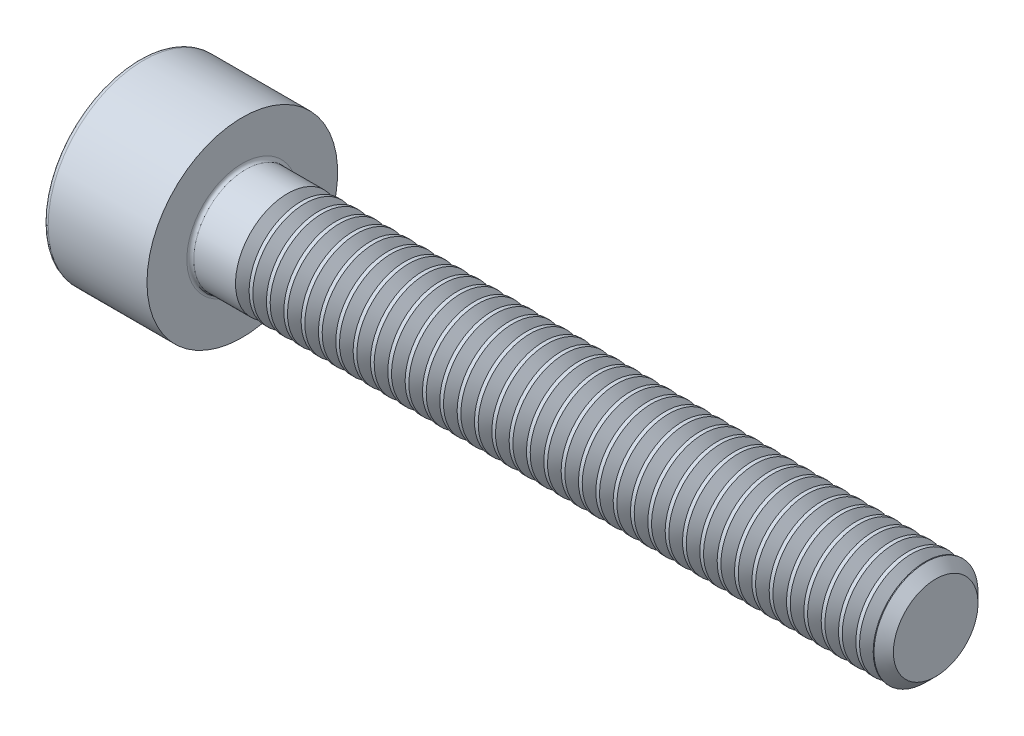
SolidWorks part; units mm, degrees
revolve "Base-Revolve" add sketch "BodySke"
sketch "BodySke" plane through (0, 0, 0) normal (0, 0, 1) x (1, 0, 0)
  line L0 (0, 0) -> (0, 2.75)
  line L1 (0, 2.75) -> (3, 2.75)
  line L2 (3, 2.75) -> (3, 1.5)
  line L3 (3, 1.5) -> (22.7195, 1.5)
  line L4 (23, 1.2195) -> (23, 0)
  line L5 (23, 0) -> (0, 0)
  line L6 (-31.75, 0) -> (127, 0) construction
  line L8 (23, 1.2195) -> (22.7195, 1.5)
  line L10 (23, -1.2195) -> (22.7195, -1.5) construction
  line L11 (3.5, 9.525) -> (3.5, 3.175) construction
  line L12 (3, 9.525) -> (3, 3.175) construction
  line L13 (-37, 9.525) -> (-37, 3.175) construction
  dimension "Body_ch_ang" = 45
  dimension "Thread_length" = 60
cosmetic thread "ThreadCosmetic" [suppressed]
fillet "Fillet1" radius 0.1 1 edges at (3, 0, 1.5)
fillet "Fillet2" radius 0.15 1 edges at (0, 0, 2.75)
ref_plane "Plane1" through (0, 0, 0) normal (0, 0, 1) x (1, 0, 0)
ref_plane "Plane2" through (0, 0, 0) normal (0, 1, 0) x (1, 0, 0)
ref_plane "Plane3" through (0, 0, 0) normal (1, 0, 0) x (0, 0, -1)
sketch "Sketch2" plane through (0, 0, 0) normal (0, 0, 1) x (1, 0, 0)
  line L0 (0, 1.28) -> (1.3, 1.28)
  line L1 (1.3, 1.28) -> (2.039, 0)
  line L2 (-31.75, 0) -> (127, 0) construction
  line L3 (2.039, 0) -> (0, 0)
  line L4 (0, 0) -> (0, 1.28)
  line L6 (0, 0) -> (47.625, 0) construction
  dimension "D2" = 60
  dimension "Depth" = 1.3
revolve "Hex-PreBroach" cut sketch "Sketch2" angle 360 about L6
sketch "Sketch3" plane through (0, 0, 0) normal (-1, 0, 0) x (0, 0.5, 0.866)
  line L0 (0.739, 1.28) -> (-0.739, 1.28)
  line L1 (-0.739, 1.28) -> (-1.478, 0)
  line L2 (0.739, 1.28) -> (1.478, 0)
  line L3 (0.739, -1.28) -> (1.478, 0)
  line L4 (0.739, -1.28) -> (-0.739, -1.28)
  line L5 (-0.739, -1.28) -> (-1.478, 0)
extrude "Hex" cut sketch "Sketch3" against normal blind 1.3
sketch "ThdSchSke" plane through (0, 0, 0) normal (0, 0, 1) x (1, 0, 0)
  line L0 (4.5, -1.2195) -> (4.3036, -1.5)
  line L1 (4.5, -1.2195) -> (4.6964, -1.5)
  line L2 (4.6964, -1.5) -> (4.6964, -1.875)
  line L3 (-3.175, 0) -> (5.1513, 0) construction
  line L4 (0, 2.6) -> (0, -2.6) construction
  line L5 (4.6964, -1.875) -> (4.3036, -1.875)
  line L6 (4.3036, -1.875) -> (4.3036, -1.5)
revolve "ThreadSchematic" cut sketch "ThdSchSke" angle 360 about L3
pattern_linear "ThdSchPat" count 37 spacing 0.5 along (1, 0, 0) of "ThreadSchematic"
equation "\"D2@Sketch3\" = \"Hex_size@Sketch3\" / 2"
equation "\"D1@Sketch3\" = \"Hex_size@Sketch3\" / 2"
equation "\"D1@Sketch2\" = \"Hex_size@Sketch3\" / 2"
equation "\"Thread_minor@ThreadCosmetic\"  =  \"Minor_dia@BodySke\""
equation "\"Depth@Sketch2\" =  \"Key_eng@Hex\""
equation "\"Thread_length@ThreadCosmetic\" = ((sgn( (\"Length@BodySke\" - \"Advance@BodySke\" * 3.0) - \"Thread_nom@BodySke\" )-1)*( (\"Length@BodySke\" - \"Advance@BodySke\" * 3.0) - \"Thread_nom@BodySke\" ))/-2+ \"Thread_nom@BodySke\""
equation "\"Thread_minor@ThdSchSke\" = \"Minor_dia@BodySke\""
equation "\"Diameter@ThdSchSke\" = \"Diameter@BodySke\""
equation "\"Overcut@ThdSchSke\" = \"Diameter@BodySke\" * 1.25"
equation "\"Start@ThdSchSke\" = \"Head_ht@BodySke\" + \"Length@BodySke\" - \"Thread_length@ThreadCosmetic\"  '---Non-countersunk---"
equation "\"Num_threads@ThdSchPat\" = int( \"Thread_length@ThreadCosmetic\" / \"Advance@BodySke\" + 0.999 )  + 1"
equation "\"Advance@ThdSchPat\" = \"Thread_length@ThreadCosmetic\" /  (\"Num_threads@ThdSchPat\" - 1) 'relax it"
equation "\"Num_threads@ThdSchPat\" = \"Num_threads@ThdSchPat\" - sgn( \"Num_threads@ThdSchPat\" - 1) '---chamfered tips only---"
